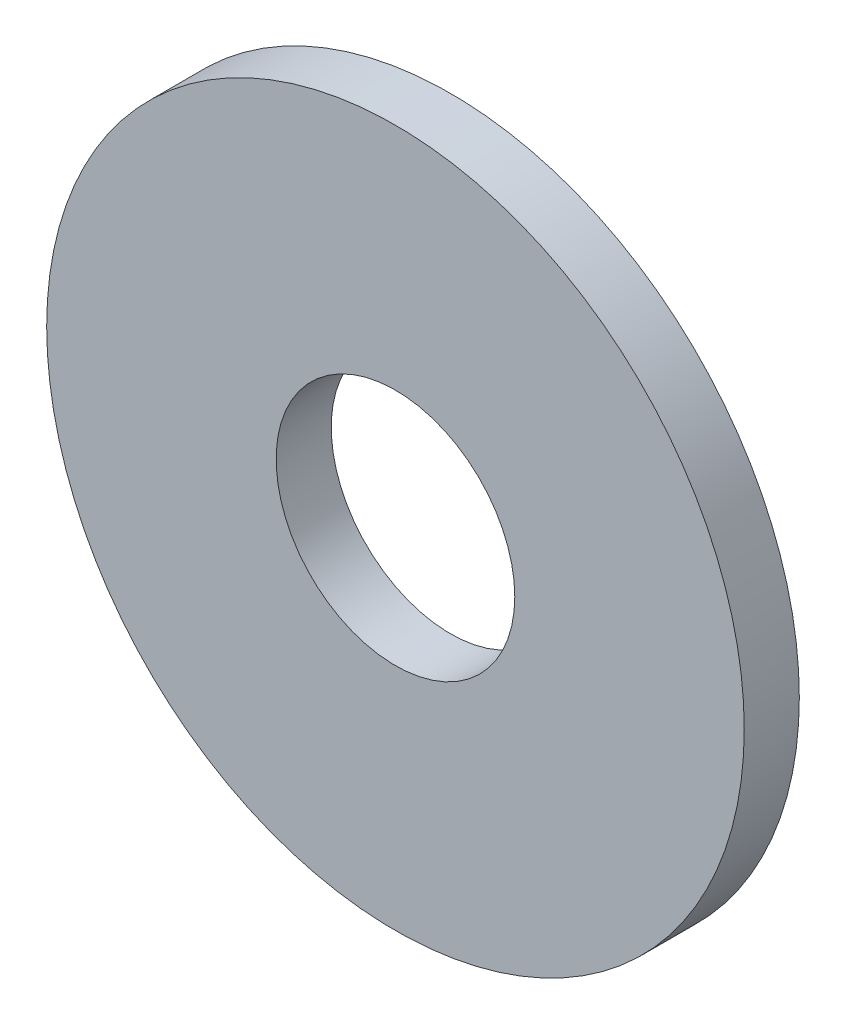
SolidWorks part; units mm, degrees
ref_plane "Top" through (0, 0, 0) normal (0, 0, 1) x (1, 0, 0)
ref_plane "Front" through (0, 0, 0) normal (0, 1, 0) x (1, 0, 0)
ref_plane "Right" through (0, 0, 0) normal (1, 0, 0) x (0, 0, -1)
sketch "Top Sketch" plane through (0, 0, 0) normal (0, 0, 1) x (1, 0, 0)
  circle A0 centre (0, 0) radius 0.65
  circle A1 centre (0, 0) radius 1.9
  dimension "Inside Diameter" = 1.3
  dimension "Outside Diameter" = 3.8
extrude "Extrude Thickness" add sketch "Top Sketch" along normal blind 0.3 contours A0
equation "\"M2 Close Fit Hole\"= 2.2"
equation "\"M2.5 Close Fit Hole\"= 2.7"
equation "\"M3 Close Fit Hole\"= 3.2"
equation "\"M4 Close Fit Hole\"= 4.3"
equation "\"M5 Close Fit Hole\"= 5.3"
equation "\"M6 Close Fit Hole\"= 6.3"
equation "\"M7 Close Fit Hole\"= 7.4"
equation "\"M8 Close Fit Hole\"= 8.4"
equation "\"M2 Tap Hole 75%\"= 1.6"
equation "\"M3 Tap Hole 75%\"= 2.5"
equation "\"M4 Tap Hole 75%\"= 3.3"
equation "\"M5 Tap Hole 75%\"= 4.2"
equation "\"M6 Tap Hole 75%\"= 5"
equation "\"M7 Tap Hole 75%\"= 6"
equation "\"M8 Tap Hole 75%\"= 6.8"
